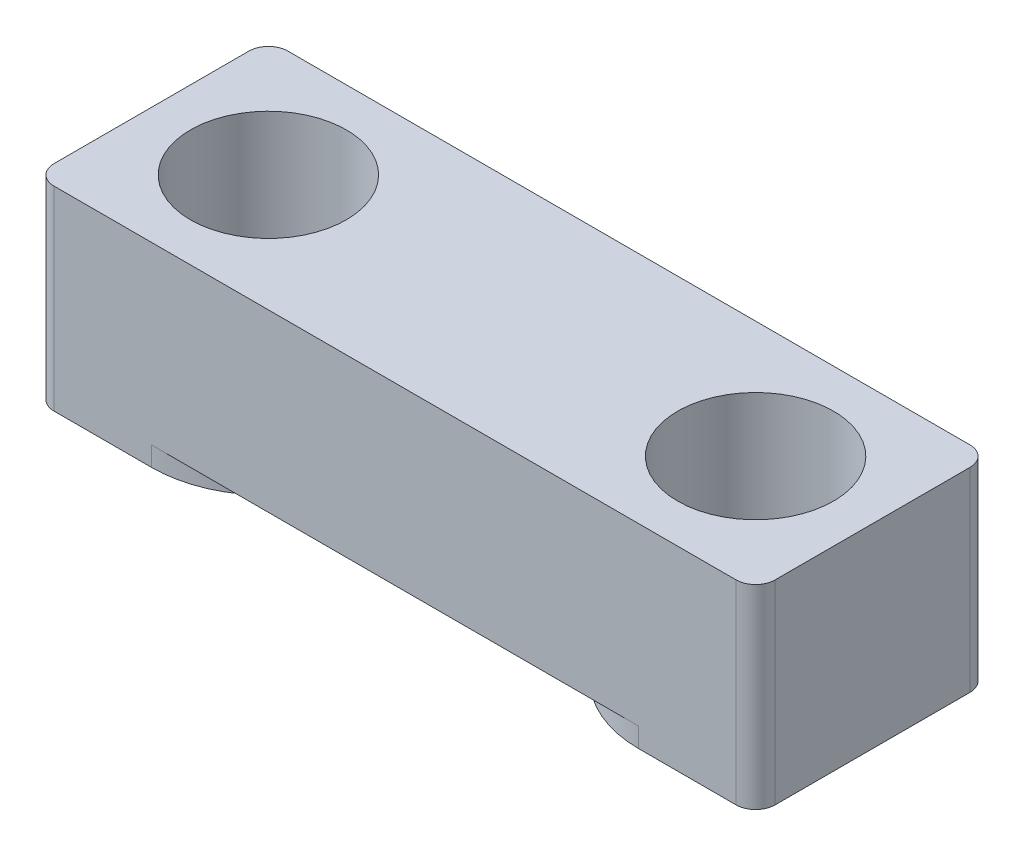
SolidWorks part; units mm, degrees
ref_plane "Front" through (0, 0, 0) normal (0, 0, 1) x (1, 0, 0)
ref_plane "Top" through (0, 0, 0) normal (0, 1, 0) x (1, 0, 0)
ref_plane "Right" through (0, 0, 0) normal (1, 0, 0) x (0, 0, -1)
sketch "Sketch1" plane through (0, 0, 0) normal (0, 1, 0) x (1, 0, 0)
  line L0 (-5, 0) -> (5, 0) construction
  line L1 (0, 0) -> (0, 2.4) construction
  line L2 (-7.4, 2.4) -> (7.4, 2.4)
  line L3 (-7.4, 2.4) -> (-7.4, -2.4)
  line L4 (-7.4, -2.4) -> (7.4, -2.4)
  line L5 (7.4, 2.4) -> (7.4, -2.4)
  line L6 (-5, 1.6) -> (-5, 2.4) construction
  circle A0 centre (-5, 0) radius 1.6
  circle A1 centre (5, 0) radius 1.6
  circle A2 centre (-5, 0) radius 2.4 construction
  point P4 (0, 0)
  dimension "D1" = 3.2
  dimension "D2" = 10
  dimension "D3" = 2.4
  dimension "D4" = 2.4
extrude "Boss-Extrude1" add sketch "Sketch1" along normal blind 4
sketch "Sketch2" plane through (0, 0, 0) normal (0, -1, 0) x (1, 0, 0)
  line L0 (-2.6, 0) -> (-2.6, -2.4) construction
  line L5 (0, 0) -> (0, -2.4) construction
  line L6 (0, 0) -> (0, -2.4) construction
  line L8 (2.6, 0) -> (2.6, -2.4) construction
  line L11 (-3.4, 0) -> (-2.6, 0) construction
  line L12 (-5, 0) -> (5, 0) construction
  line L17 (-7.4, 2.4) -> (-7.4, -2.4)
  line L18 (-7.4, -2.4) -> (7.4, -2.4)
  line L19 (7.4, -2.4) -> (7.4, 2.4)
  line L20 (7.4, 2.4) -> (-7.4, 2.4)
  line L22 (-5, -2.4) -> (5, -2.4)
  line L24 (5, 2.4) -> (-5, 2.4)
  circle A1 centre (-5, 0) radius 1.6 construction
  arc A2 (-5, -2.4) -> (-5, 2.4) centre (-5, 0) ccw
  arc A3 (5, 2.4) -> (5, -2.4) centre (5, 0) ccw
  circle A4 centre (5, 0) radius 1.6 construction
  dimension "D5" = 0.8
  dimension "D2" = 0
  dimension "D1" = 0.8
extrude "Cut-Extrude2" cut sketch "Sketch2" against normal blind 0.4
sketch "Sketch3" plane through (0, 0, 0) normal (0, -1, 0) x (1, 0, 0)
  circle A0 centre (5, 0) radius 1.6 construction
  circle A1 centre (-5, 0) radius 1.6 construction
  circle A2 centre (5, 0) radius 1.6
  circle A3 centre (-5, 0) radius 1.6
  circle A4 centre (-5, 0) radius 1.1
  circle A5 centre (5, 0) radius 1.1
  dimension "D2" = 2.2
  dimension "D1" = 0.5
extrude "Boss-Extrude2" add sketch "Sketch3" against normal offset from surface (1 mm away) 3 up to face at (-5, 4, 1.6)
fillet "Fillet1" radius 0.4 4 edges at (-7.4, 2, -2.4) (7.4, 2, -2.4) (7.4, 2, 2.4) (-7.4, 2, 2.4)
